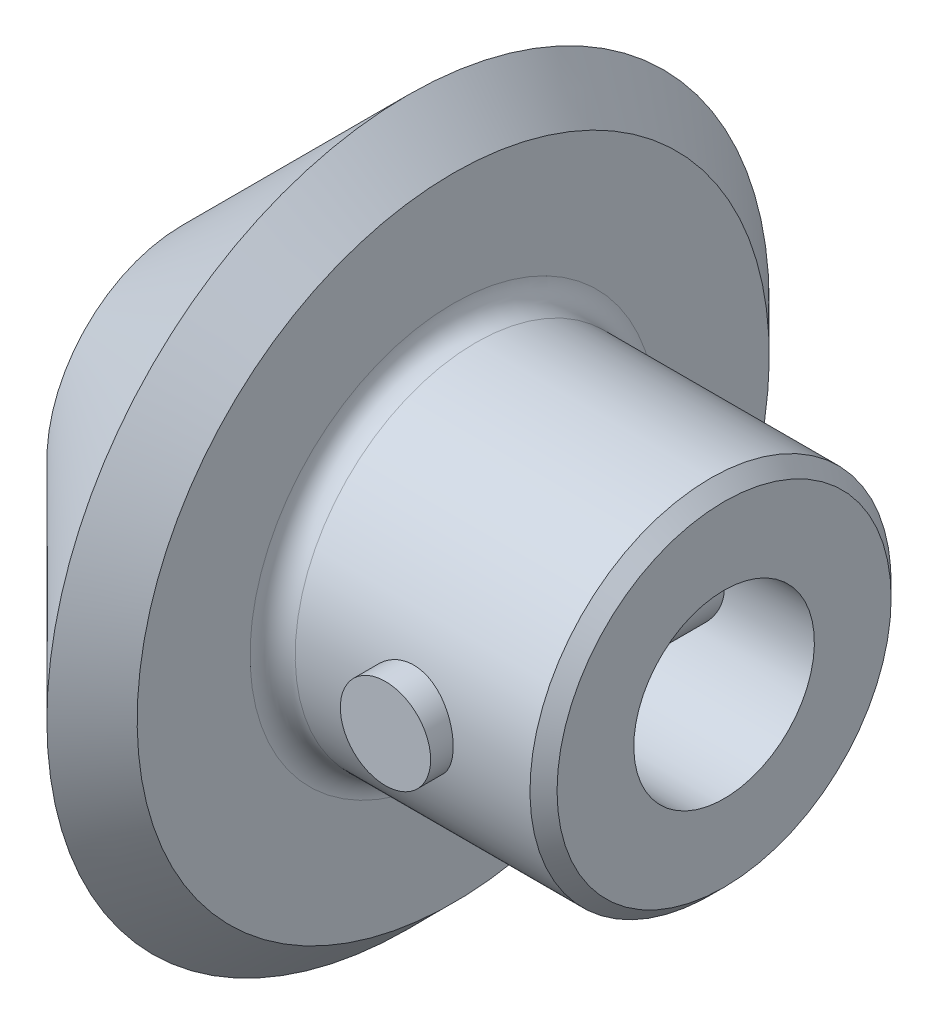
SolidWorks part; units mm, degrees
ref_plane "Front Plane" through (0, 0, 0) normal (0, 0, 1) x (1, 0, 0)
ref_plane "Top Plane" through (0, 0, 0) normal (0, 1, 0) x (1, 0, 0)
ref_plane "Right Plane" through (0, 0, 0) normal (1, 0, 0) x (0, 0, -1)
sketch "Sketch1" plane through (0, 0, 0) normal (0, 0, 1) x (1, 0, 0)
  line L0 (0, 0) -> (0, 3)
  line L1 (0, 3) -> (5, 8)
  line L2 (5, 8) -> (6, 7)
  line L3 (6, 7) -> (6, 0)
  line L4 (6, 0) -> (0, 0)
  dimension "D1" = 8
  dimension "D2" = 1
  dimension "D3" = 5
  dimension "D4" = 45
  dimension "D5" = 45
revolve "Revolve1" add sketch "Sketch1" angle 360 about L4
sketch "Sketch2" plane through (0, 0, 0) normal (-1, 0, 0) x (0, 0, 1)
  circle A0 centre (0, 0) radius 1.5
  dimension "D1" = 3
extrude "Cut-Extrude1" cut sketch "Sketch2" against normal blind 10
sketch "Sketch3" plane through (6, 0, 0) normal (1, 0, 0) x (0, 0, -1)
  circle A0 centre (0, 0) radius 4
  dimension "D1" = 8
extrude "Boss-Extrude1" add sketch "Sketch3" along normal blind 6
sketch "Sketch4" plane through (12, 0, 0) normal (1, 0, 0) x (0, 0, -1)
  circle A0 centre (0, 0) radius 2
  dimension "D1" = 4
extrude "Cut-Extrude2" cut sketch "Sketch4" against normal blind 6
sketch "Sketch5" plane through (0, 0, 0) normal (0, 0, 1) x (1, 0, 0)
  line L0 (12, -4) -> (12, 4) construction
  circle A0 centre (9, 0) radius 1
  dimension "D1" = 2
  dimension "D2" = 3
extrude "Cut-Extrude3" cut sketch "Sketch5" against normal through all both and the other way through all
fillet "Fillet1" radius 0.5 1 edges at (6, 4, 0)
chamfer "Chamfer1" distance 0.3 angle 45 1 edges at (12, 4, 0)
sketch "Sketch6" plane through (0, 0, 0) normal (0, 0, 1) x (1, 0, 0)
  circle A0 centre (9, 0) radius 1 construction
  circle A1 centre (9, 0) radius 1
extrude "Boss-Extrude2" add sketch "Sketch6" along normal mid plane 9 separate body
